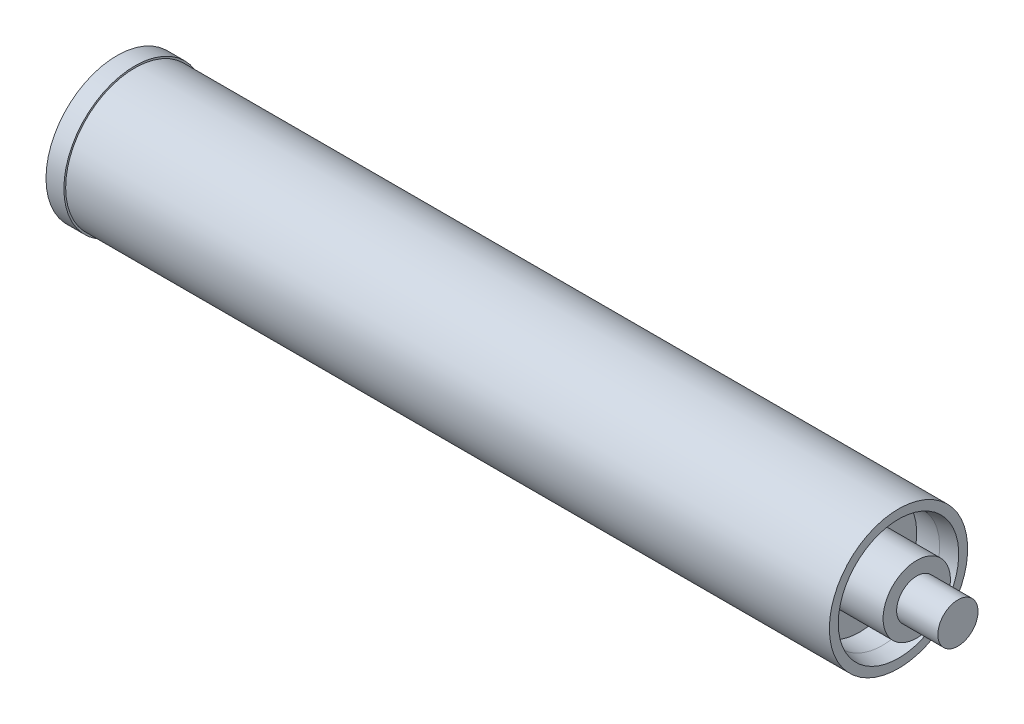
SolidWorks part; units mm, degrees
material "1060 Alloy"
ref_plane "Plan de face" through (0, 0, 0) normal (0, 0, 1) x (1, 0, 0)
ref_plane "Plan de dessus" through (0, 0, 0) normal (0, 1, 0) x (1, 0, 0)
ref_plane "Plan de droite" through (0, 0, 0) normal (1, 0, 0) x (0, 0, -1)
sketch "Esquisse2" plane through (0, 0, 0) normal (0, 0, 1) x (1, 0, 0)
  line L0 (0, 0) -> (97.8436, 0) construction
  line L1 (0, -26) -> (0, 26) construction
  line L2 (0, 26) -> (12.7, 26)
  line L3 (12.7, 26) -> (12.7, 50.419) construction
  line L4 (12.7, 50.419) -> (25.4, 50.419)
  line L5 (25.4, 50.419) -> (25.4, 49.149)
  line L6 (25.4, 49.149) -> (568.32, 49.149)
  line L7 (568.32, 49.149) -> (568.32, 42.8202)
  line L8 (568.32, 42.8202) -> (556.9971, 40.5731)
  line L9 (556.9971, 40.5731) -> (540.71, 40.5731)
  line L10 (540.71, 40.5731) -> (540.71, 23.9395)
  line L11 (540.71, 23.9395) -> (581.28, 23.9395)
  line L12 (581.28, 23.9395) -> (581.28, 14.2875)
  line L13 (581.28, 14.2875) -> (610.57, 14.2875)
  line L14 (610.57, 14.2875) -> (610.57, -14.2875) construction
  line L15 (610.57, 0) -> (0, 0) construction
  line L16 (581.28, -14.2875) -> (610.57, -14.2875) construction
  line L17 (581.28, -23.9395) -> (581.28, -14.2875) construction
  line L18 (540.71, -23.9395) -> (581.28, -23.9395) construction
  line L19 (540.71, -40.5731) -> (540.71, -23.9395) construction
  line L20 (556.9971, -40.5731) -> (540.71, -40.5731) construction
  line L21 (568.32, -42.8202) -> (556.9971, -40.5731) construction
  line L22 (568.32, -49.149) -> (568.32, -42.8202) construction
  line L23 (25.4, -49.149) -> (568.32, -49.149) construction
  line L24 (25.4, -50.419) -> (25.4, -49.149) construction
  line L25 (12.7, -50.419) -> (25.4, -50.419) construction
  line L26 (12.7, -26) -> (12.7, -50.419) construction
  line L27 (0, -26) -> (12.7, -26) construction
  line L28 (12.7, 50.419) -> (12.7, 38.2095)
  line L29 (12.7, 38.2095) -> (25.4, 35.6891)
  line L30 (25.4, 35.6891) -> (36.5674, 35.6891)
  line L31 (36.5674, 35.6891) -> (36.5674, 26)
  line L32 (36.5674, 26) -> (12.7, 26)
  line L33 (25.4, 35.6891) -> (25.4, 49.149) construction
  line L34 (36.5674, -26) -> (12.7, -26) construction
  line L35 (36.5674, -35.6891) -> (36.5674, -26) construction
  line L36 (25.4, -35.6891) -> (36.5674, -35.6891) construction
  line L37 (12.7, -38.2095) -> (25.4, -35.6891) construction
  line L38 (12.7, -50.419) -> (12.7, -38.2095) construction
  line L39 (0, 26) -> (0, 0)
  line L40 (0, 0) -> (610.57, 0)
  line L41 (610.57, 0) -> (610.57, 14.2875)
  dimension "D1" = 597.87
  dimension "D2" = 568.58
  dimension "D3" = 555.62
  dimension "D4" = 28.575
  dimension "D5" = 47.879
  dimension "D6" = 98.298
  dimension "D7" = 12.7
  dimension "D8" = 100.838
  dimension "D9" = 12.7
  dimension "D10" = 52
  dimension "D11" = 40.57
revolve "Révolution7" add sketch "Esquisse2" angle 360 about L0
sketch "Esquisse3" plane through (0, 0, 0) normal (0, 0, 1) x (1, 0, 0)
  line L0 (0, 0) -> (610.57, 0) construction
  line L1 (610.57, -14.2875) -> (610.57, 14.2875) construction
  line L2 (0, 20) -> (0, 0)
  line L3 (0, 26) -> (0, -26) construction
  line L4 (0, 0) -> (540.71, 0)
  line L5 (540.71, 0) -> (540.71, 12.9578)
  line L6 (540.71, -40.5731) -> (540.71, 40.5731) construction
  line L7 (540.71, 12.9578) -> (381.0611, 12.9578)
  line L8 (381.0611, 12.9578) -> (381.0611, 44.271)
  line L9 (381.0611, 44.271) -> (65.8719, 44.271)
  line L10 (65.8719, 44.271) -> (34.083, 14.3276)
  line L11 (34.083, 14.3276) -> (19.083, 14.3276)
  line L12 (19.083, 14.3276) -> (0, 20)
  line L13 (36.5674, 26) -> (0, 26) construction
  dimension "D1" = 15
  dimension "D2" = 6
revolve "Enlèvement de matière-Révolution1" cut sketch "Esquisse3" angle 360 about L0
